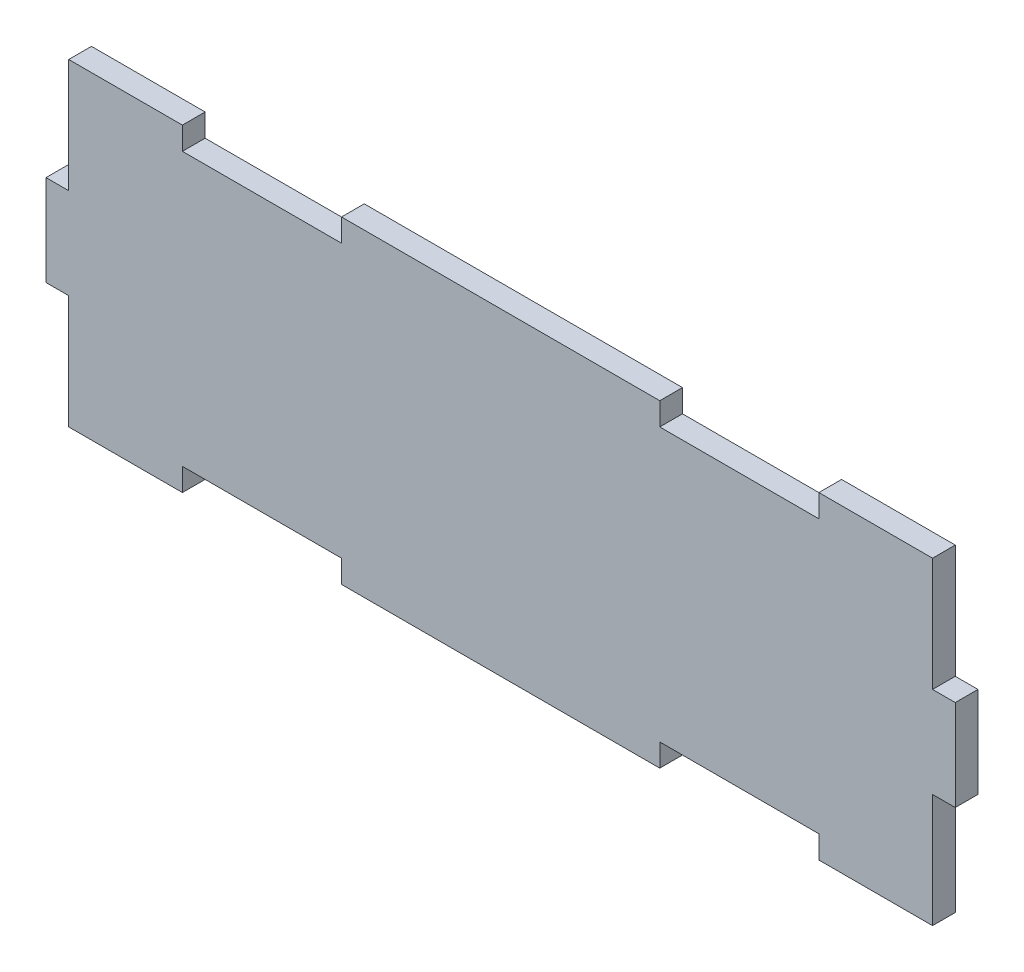
SolidWorks part; units mm, degrees
ref_plane "Plan de face" through (0, 0, 0) normal (0, 0, 1) x (1, 0, 0)
ref_plane "Plan de dessus" through (0, 0, 0) normal (0, 1, 0) x (1, 0, 0)
ref_plane "Plan de droite" through (0, 0, 0) normal (1, 0, 0) x (0, 0, -1)
sketch "Esquisse1" plane through (0, 0, 0) normal (0, 0, 1) x (1, 0, 0)
  line L0 (-48.0462, 55.6933) -> (21.9538, 55.6933)
  line L1 (21.9538, 55.6933) -> (21.9538, 50.6933)
  line L2 (21.9538, 50.6933) -> (56.9538, 50.6933)
  line L3 (56.9538, 50.6933) -> (56.9538, 55.6933)
  line L4 (56.9538, 55.6933) -> (81.9538, 55.6933)
  line L5 (81.9538, 55.6933) -> (81.9538, 30.6933)
  line L6 (81.9538, 30.6933) -> (86.9538, 30.6933)
  line L7 (86.9538, 30.6933) -> (86.9538, 10.6933)
  line L8 (-13.0462, 55.6933) -> (-13.0462, 20.6933) construction
  line L9 (-13.0462, 20.6933) -> (86.9538, 20.6933) construction
  line L10 (-48.0462, -14.3067) -> (21.9538, -14.3067)
  line L11 (81.9538, 10.6933) -> (86.9538, 10.6933)
  line L12 (81.9538, -14.3067) -> (81.9538, 10.6933)
  line L13 (56.9538, -14.3067) -> (81.9538, -14.3067)
  line L14 (56.9538, -9.3067) -> (56.9538, -14.3067)
  line L15 (21.9538, -9.3067) -> (56.9538, -9.3067)
  line L16 (21.9538, -14.3067) -> (21.9538, -9.3067)
  line L17 (-48.0462, -14.3067) -> (-48.0462, -9.3067)
  line L18 (-48.0462, -9.3067) -> (-83.0462, -9.3067)
  line L19 (-83.0462, -9.3067) -> (-83.0462, -14.3067)
  line L20 (-83.0462, -14.3067) -> (-108.0462, -14.3067)
  line L21 (-108.0462, -14.3067) -> (-108.0462, 10.6933)
  line L22 (-108.0462, 10.6933) -> (-113.0462, 10.6933)
  line L23 (-113.0462, 30.6933) -> (-113.0462, 10.6933)
  line L24 (-108.0462, 30.6933) -> (-113.0462, 30.6933)
  line L25 (-108.0462, 55.6933) -> (-108.0462, 30.6933)
  line L26 (-83.0462, 55.6933) -> (-108.0462, 55.6933)
  line L27 (-83.0462, 50.6933) -> (-83.0462, 55.6933)
  line L28 (-48.0462, 50.6933) -> (-83.0462, 50.6933)
  line L29 (-48.0462, 55.6933) -> (-48.0462, 50.6933)
  point P20 (-13.0462, -14.3067)
  dimension "D1" = 95
  dimension "D2" = 35
  dimension "D3" = 35
  dimension "D4" = 5
  dimension "D5" = 25
  dimension "D6" = 10
extrude "Boss.-Extru.1" add sketch "Esquisse1" along normal blind 5
